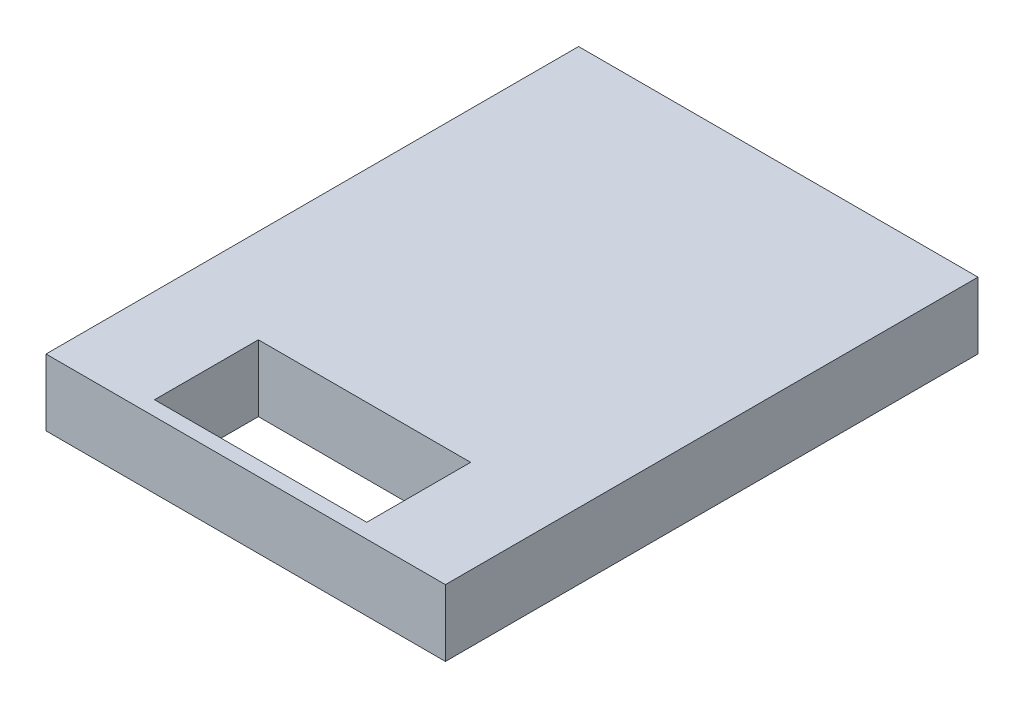
SolidWorks part; units mm, degrees
ref_plane "Front Plane" through (0, 0, 0) normal (0, 0, 1) x (1, 0, 0)
ref_plane "Top Plane" through (0, 0, 0) normal (0, 1, 0) x (1, 0, 0)
ref_plane "Right Plane" through (0, 0, 0) normal (1, 0, 0) x (0, 0, -1)
sketch "Sketch1" plane through (0, 0, 0) normal (0, 1, 0) x (1, 0, 0)
  line L0 (0, 0) -> (76.2, 0)
  line L1 (0, 0) -> (0, 101.6)
  line L2 (0, 101.6) -> (76.2, 101.6)
  line L3 (76.2, 101.6) -> (76.2, 0)
  line L4 (17.907, 22.606) -> (17.907, 2.794)
  line L7 (17.907, 22.606) -> (58.3984, 22.606)
  line L8 (58.3984, 22.606) -> (58.3984, 2.794)
  line L9 (58.3984, 2.794) -> (17.907, 2.794)
  dimension "D1" = 76.2
  dimension "D2" = 101.6
  dimension "D3" = 19.812
  dimension "D4" = 40.4914
  dimension "D5" = 78.994
  dimension "D6" = 17.907
extrude "Boss-Extrude1" add sketch "Sketch1" along normal blind 12.7
